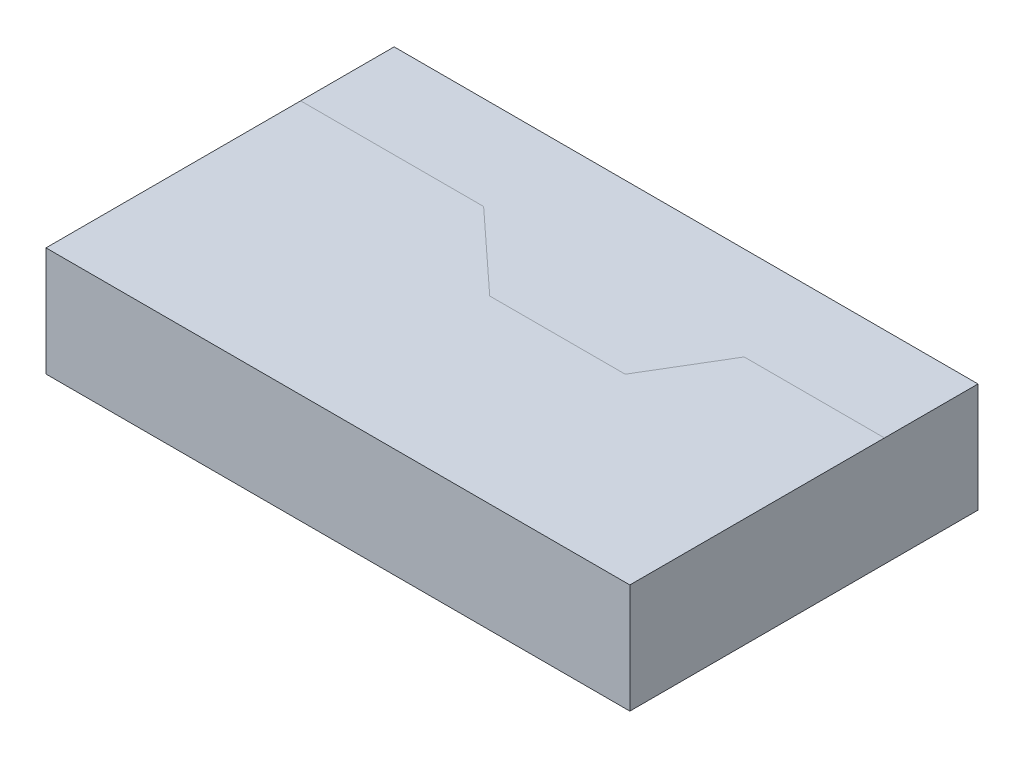
SolidWorks part; units mm, degrees
ref_plane "Front Plane" through (0, 0, 0) normal (0, 0, 1) x (1, 0, 0)
ref_plane "Top Plane" through (0, 0, 0) normal (0, 1, 0) x (1, 0, 0)
ref_plane "Right Plane" through (0, 0, 0) normal (1, 0, 0) x (0, 0, -1)
sketch "Sketch1" plane through (0, 0, 0) normal (0, 1, 0) x (1, 0, 0)
  line L1 (0, 0) -> (135.6762, 0)
  line L2 (0, 0) -> (0, 80.901)
  line L3 (0, 80.901) -> (135.6762, 80.901)
  line L4 (135.6762, 0) -> (135.6762, 80.901)
extrude "Extrude1" add sketch "Sketch1" against normal blind 25.4
sketch "Sketch2" plane through (0, 0, 0) normal (0, 1, 0) x (1, 0, 0)
  line L0 (42.5239, 59.1702) -> (0, 59.1702)
  line L1 (42.5239, 59.1702) -> (61.2436, 41.8687)
  line L2 (61.2436, 41.8687) -> (92.7268, 41.8687)
  line L3 (92.7268, 41.8687) -> (103.0794, 59.1702)
  line L4 (103.0794, 59.1702) -> (135.6762, 59.1702)
  line L5 (135.6762, 0) -> (135.6762, 80.901) construction
  line L6 (0, 80.901) -> (0, 0) construction
split line "Split Line1"
